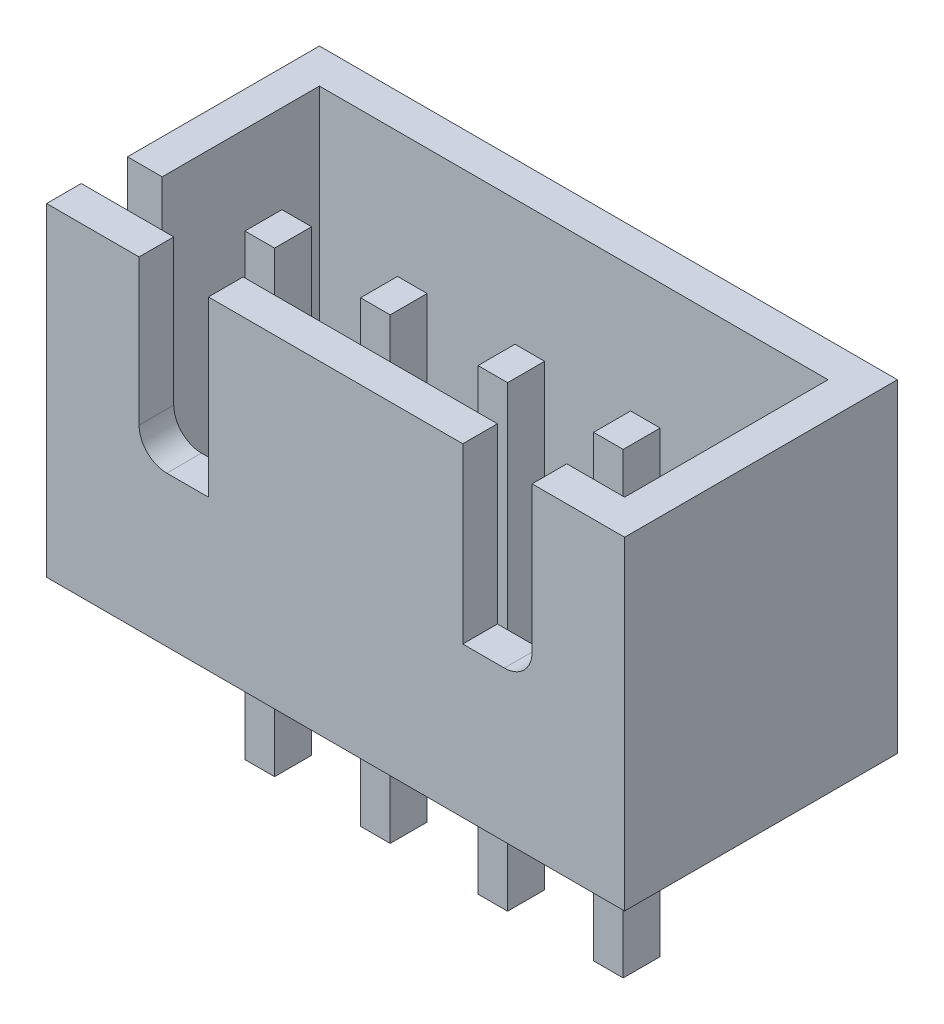
SolidWorks part; units mm, degrees
ref_plane "Alzado" through (0, 0, 0) normal (0, 0, 1) x (1, 0, 0)
ref_plane "Planta" through (0, 0, 0) normal (0, 1, 0) x (1, 0, 0)
ref_plane "Vista lateral" through (0, 0, 0) normal (1, 0, 0) x (0, 0, -1)
sketch "Croquis1" plane through (0, 0, 0) normal (0, 1, 0) x (1, 0, 0)
  line L0 (-2.48, 3.37) -> (10.02, 3.37)
  line L1 (10.02, 3.37) -> (10.02, -2.53)
  line L2 (10.02, -2.53) -> (-2.48, -2.53)
  line L3 (-2.48, -2.53) -> (-2.48, 3.37)
  line L4 (3.77, -2.53) -> (3.77, 2.1284) construction
  line L5 (-0.32, -0.4) -> (0.32, -0.4)
  line L6 (-0.32, -0.4) -> (-0.32, 0.4)
  line L7 (-0.32, 0.4) -> (0.32, 0.4)
  line L8 (0.32, -0.4) -> (0.32, 0.4)
  line L9 (-0.32, -0.4) -> (0.32, 0.4) construction
  line L10 (-0.32, 0.4) -> (0.32, -0.4) construction
  line L11 (7.86, -0.4) -> (7.86, 0.4)
  line L12 (7.86, -0.4) -> (7.22, -0.4)
  line L13 (7.22, -0.4) -> (7.22, 0.4)
  line L14 (7.86, 0.4) -> (7.22, 0.4)
  line L15 (4.72, -0.4) -> (4.72, 0.4)
  line L16 (2.18, -0.4) -> (2.82, -0.4)
  line L17 (2.18, -0.4) -> (2.18, 0.4)
  line L18 (2.18, 0.4) -> (2.82, 0.4)
  line L19 (2.82, -0.4) -> (2.82, 0.4)
  line L20 (2.18, -0.4) -> (2.82, 0.4) construction
  line L21 (2.18, 0.4) -> (2.82, -0.4) construction
  line L22 (5.36, 0.4) -> (4.72, 0.4)
  line L23 (5.36, -0.4) -> (5.36, 0.4)
  line L24 (5.36, -0.4) -> (4.72, -0.4)
  point P5 (0, 0)
  point P16 (2.5, 0)
  point P21 (0, 0)
  point P22 (2.9417, 0)
  point P27 (5.04, 0)
  point P28 (0, 0)
  dimension "D1" = 12.5
  dimension "D2" = 5.9
  dimension "D3" = 3.37
  dimension "D4" = 2.48
  dimension "D5" = 0.8
  dimension "D6" = 0.64
  dimension "D7" = 2.5
extrude "Saliente-Extruir1" add sketch "Croquis1" along normal blind 1
sketch "Croquis2" plane through (0, 1, 0) normal (0, 1, 0) x (1, 0, 0)
  line L1 (-1.73, -1.78) -> (9.27, -1.78)
  line L2 (-1.73, -1.78) -> (-1.73, 2.62)
  line L3 (-1.73, 2.62) -> (9.27, 2.62)
  line L4 (-2.48, 3.37) -> (-2.48, -2.53)
  line L5 (-2.48, -2.53) -> (10.02, -2.53)
  line L6 (10.02, -2.53) -> (10.02, 3.37)
  line L7 (10.02, 3.37) -> (-2.48, 3.37)
  line L8 (-2.48, 3.37) -> (-2.48, -2.53)
  line L9 (-2.48, -2.53) -> (10.02, -2.53)
  line L10 (10.02, -2.53) -> (10.02, 3.37)
  line L11 (10.02, 3.37) -> (-2.48, 3.37)
  line L12 (9.27, -1.78) -> (9.27, 2.62)
  line L13 (-1.73, -1.78) -> (9.27, 2.62) construction
  line L14 (-1.73, 2.62) -> (9.27, -1.78) construction
  point P2 (3.77, 0.42)
  dimension "D2" = 0.75
  dimension "D3" = 0.75
  dimension "D4" = 0.75
  dimension "D5" = 0.75
  dimension "D1" = 0
extrude "Saliente-Extruir2" add sketch "Croquis2" along normal blind 6
sketch "Croquis3" plane through (-2.48, 0, 0) normal (-1, 0, 0) x (0, 0, 1)
  line L0 (1.78, 7) -> (1.78, 4.35)
  line L1 (-3.37, 7) -> (2.53, 7) construction
  line L2 (0.78, 3.75) -> (0.78, 7)
  line L3 (2.53, 7) -> (2.53, 0) construction
  line L4 (1.18, 3.75) -> (0.78, 3.75)
  line L5 (0.78, 7) -> (1.78, 7)
  arc A1 (1.18, 3.75) -> (1.78, 4.35) centre (1.18, 4.35) ccw
  dimension "D4" = 0.6
  dimension "D1" = 0.75
  dimension "D2" = 1
  dimension "D3" = 3.25
extrude "Cortar-Extruir1" cut sketch "Croquis3" against normal blind 9
sketch "Croquis4" plane through (0, 0, 2.53) normal (0, 0, 1) x (1, 0, 0)
  line L0 (-0.48, 3.85) -> (-0.48, 7)
  line L1 (-2.48, 7) -> (10.02, 7) construction
  line L3 (8.02, 3.85) -> (8.02, 7)
  line L4 (10.02, 7) -> (10.02, 0) construction
  line L5 (3.77, 0) -> (3.77, 7) construction
  line L6 (-2.48, 0) -> (10.02, 0) construction
  line L7 (-0.48, 7) -> (8.02, 7)
  line L8 (6.52, 3.25) -> (6.52, 7)
  line L9 (6.52, 3.25) -> (7.42, 3.25)
  line L10 (1.02, 3.25) -> (1.02, 7)
  line L11 (1.02, 3.25) -> (0.12, 3.25)
  arc A0 (7.42, 3.25) -> (8.02, 3.85) centre (7.42, 3.85) ccw
  arc A1 (0.12, 3.25) -> (-0.48, 3.85) centre (0.12, 3.85) cw
  point P18 (3.77, 3.25)
  point P21 (0, 0)
  point P22 (0, 0)
  line M11 (10.02, 7) -> (-2.48, 7)
  dimension "D2" = 0.6
  dimension "D1" = 2
  dimension "D3" = 3.75
  dimension "D4" = 1.5
extrude "Cortar-Extruir2" cut sketch "Croquis4" against normal blind 2 contours A1 L11 L10 L0 M11 | L9 A0 L3 L8 M11
sketch "Croquis5" plane through (0, 0, 0) normal (0, 1, 0) x (1, 0, 0)
  line L0 (7.86, -0.4) -> (7.86, 0.4) construction
  line L1 (7.22, -0.4) -> (7.86, -0.4) construction
  line L2 (7.22, 0.4) -> (7.22, -0.4) construction
  line L3 (7.86, 0.4) -> (7.22, 0.4) construction
  line L4 (0.32, 0.4) -> (-0.32, 0.4) construction
  line L5 (0.32, -0.4) -> (0.32, 0.4) construction
  line L6 (-0.32, -0.4) -> (0.32, -0.4) construction
  line L7 (-0.32, 0.4) -> (-0.32, -0.4) construction
  line L8 (7.86, -0.4) -> (7.86, 0.4)
  line L9 (7.22, -0.4) -> (7.86, -0.4)
  line L10 (7.22, 0.4) -> (7.22, -0.4)
  line L11 (7.86, 0.4) -> (7.22, 0.4)
  line L12 (0.32, 0.4) -> (-0.32, 0.4)
  line L13 (0.32, -0.4) -> (0.32, 0.4)
  line L14 (-0.32, -0.4) -> (0.32, -0.4)
  line L15 (-0.32, 0.4) -> (-0.32, -0.4)
  line L16 (2.82, -0.4) -> (2.82, 0.4) construction
  line L17 (2.18, -0.4) -> (2.82, -0.4) construction
  line L18 (2.18, 0.4) -> (2.18, -0.4) construction
  line L19 (2.82, 0.4) -> (2.18, 0.4) construction
  line L20 (2.82, -0.4) -> (2.82, 0.4)
  line L21 (2.18, -0.4) -> (2.82, -0.4)
  line L22 (2.18, 0.4) -> (2.18, -0.4)
  line L23 (2.82, 0.4) -> (2.18, 0.4)
  line L24 (4.72, -0.4) -> (5.36, -0.4) construction
  line L25 (4.72, 0.4) -> (4.72, -0.4) construction
  line L26 (5.36, 0.4) -> (4.72, 0.4) construction
  line L27 (5.36, -0.4) -> (5.36, 0.4) construction
  line L28 (4.72, -0.4) -> (5.36, -0.4)
  line L29 (4.72, 0.4) -> (4.72, -0.4)
  line L30 (5.36, 0.4) -> (4.72, 0.4)
  line L31 (5.36, -0.4) -> (5.36, 0.4)
extrude "Saliente-Extruir3" add sketch "Croquis5" along normal blind 6.5 and the other way blind 3.4
